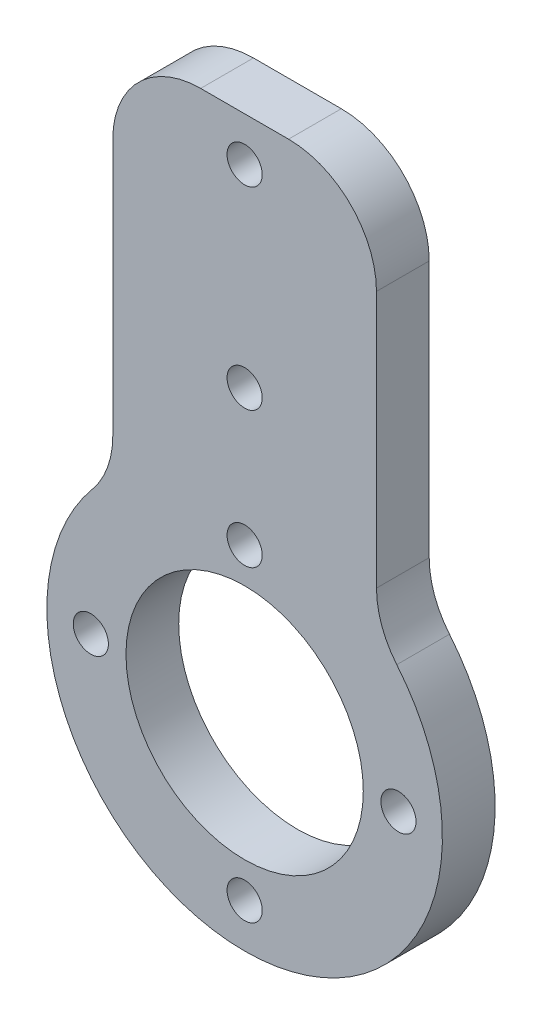
SolidWorks part; units mm, degrees
ref_plane "Front Plane" through (0, 0, 0) normal (0, 0, 1) x (1, 0, 0)
ref_plane "Top Plane" through (0, 0, 0) normal (0, 1, 0) x (1, 0, 0)
ref_plane "Right Plane" through (0, 0, 0) normal (1, 0, 0) x (0, 0, -1)
sketch "Sketch1" plane through (0, 0, 0) normal (0, 0, 1) x (1, 0, 0)
  line L0 (-15, 60) -> (15, 60)
  line L3 (-15, 60) -> (-15, 16.7705)
  line L4 (15, 60) -> (15, 16.7705)
  circle A0 centre (0, 0) radius 22.5
  circle A1 centre (0, 0) radius 13.5
  circle A2 centre (0, 17.5) radius 2
  circle A3 centre (17.5, 0) radius 2
  circle A4 centre (0, -17.5) radius 2
  circle A5 centre (-17.5, 0) radius 2
  circle A6 centre (0, 55) radius 2
  circle A7 centre (0, 33) radius 2
  point P10 (0, 60)
  point P17 (0, 0)
  dimension "D1" = 45
  dimension "D3" = 27
  dimension "D4" = 4
  dimension "D8" = 4
  dimension "D9" = 4
  dimension "D2" = 60
  dimension "D5" = 17.5
  dimension "D7" = 30
  dimension "D10" = 5
  dimension "D11" = 22
  dimension "D6" = 4
extrude "Boss-Extrude1" add sketch "Sketch1" along normal mid plane 6 contours A0 L4 L0 L3 | A0 A5 A4 A3 A2 A1
fillet "Fillet1" radius 10 4 edges at (15, 60, 0) (-15, 60, 0) (15, 16.7705, 0) (-15, 16.7705, 0)
